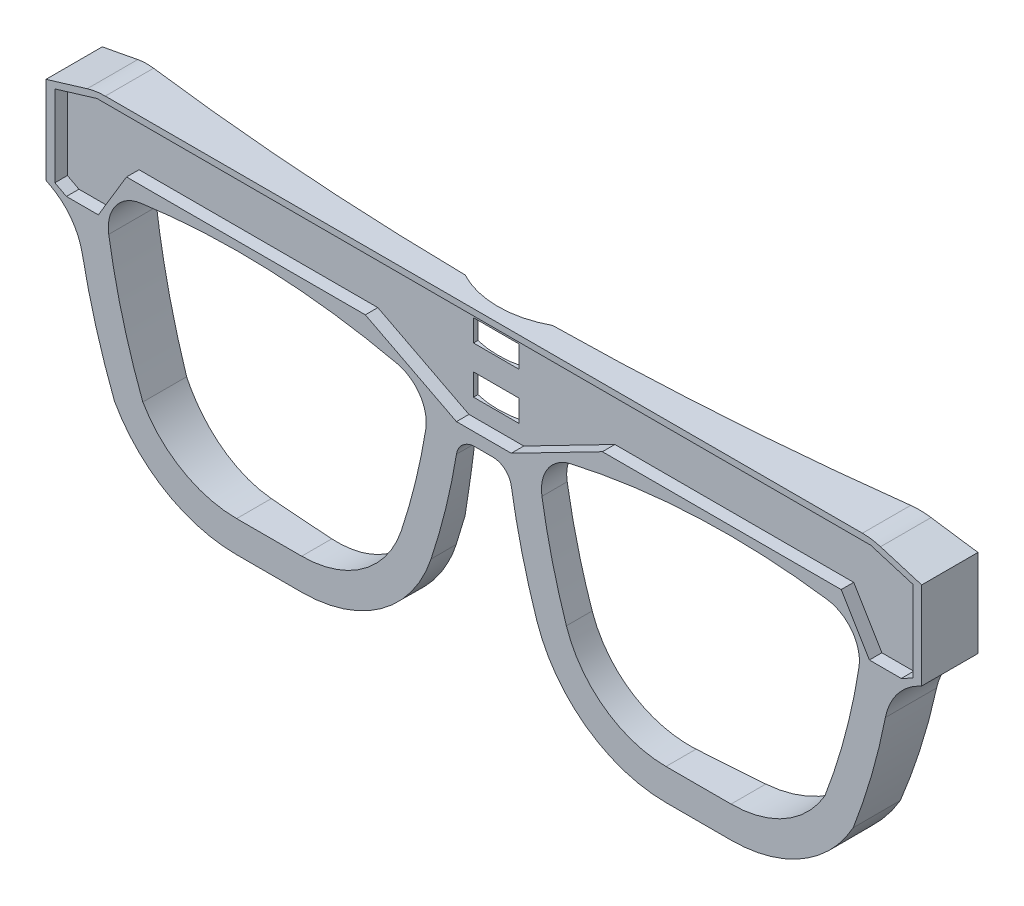
SolidWorks part; units mm, degrees
ref_plane "Front Plane" through (0, 0, 0) normal (0, 0, 1) x (1, 0, 0)
ref_plane "Top Plane" through (0, 0, 0) normal (0, 1, 0) x (1, 0, 0)
ref_plane "Right Plane" through (0, 0, 0) normal (1, 0, 0) x (0, 0, -1)
sketch "Sketch1" plane through (0, 0, 0) normal (0, 0, 1) x (1, 0, 0)
  line L4 (-70, 16.5826) -> (-70, 2.5826)
  line L5 (-70, 2.5826) -> (-65, -0.0353)
  line L6 (-39.5244, -34) -> (-29.1194, -34)
  line L7 (-4, 0) -> (0, 0)
  line L8 (0, 45.3197) -> (0, -37.9766) construction
  line L11 (-62, 19) -> (0, 19)
  line L12 (0, 19) -> (0, 0)
  line L13 (-70, 16.5826) -> (-62, 19)
  arc A2 (-8.4439, -19.0581) -> (-4, 0) centre (-111.6609, 15.057) ccw
  arc A3 (-65, -0.0353) -> (-59.0574, -22.499) centre (40.965, 15.9791) ccw
  arc A4 (-59.0574, -22.499) -> (-39.5244, -34) centre (-39.5244, -11.6623) ccw
  arc A5 (-29.1194, -34) -> (-8.4439, -19.0581) centre (-29.1194, -12.2244) ccw
  point P4 (-65, 21)
  point P7 (0, 0)
  point P20 (0, -37.9766)
  point P21 (-65, 19)
  point P22 (-70, 14.7143)
  point P23 (0, 0)
  point P24 (-70, 16.5826)
  dimension "D8" = 5
  dimension "D1" = 4
  dimension "D2" = 53
  dimension "D3" = 34
  dimension "D4" = 70
  dimension "D5" = 8
  dimension "D7" = 14
extrude "Boss-Extrude1" add sketch "Sketch1" along normal blind 9 contours L4 L5 A3 A4 L6 A5 A2 L7 L12 L11 L13
sketch "Sketch2" plane through (0, 0, 9) normal (0, 0, 1) x (1, 0, 0)
  line L7 (-39.5244, -29) -> (-29.1194, -29)
  line L8 (-39.5244, -29) -> (-29.1194, -29)
  arc A15 (-60.0561, 0.7118) -> (-59.2887, 6.3037) centre (-50.178, 2.2047) cw
  arc A16 (-59.2887, 6.3037) -> (-8.9375, 4.059) centre (-39.064, -105.8745) cw
  arc A17 (-8.9375, 4.059) -> (-8.9518, 0.6925) centre (-21.3647, 2.4286) cw
  arc A19 (-13.1913, -17.489) -> (-8.9518, 0.6925) centre (-111.6609, 15.057) ccw
  arc A20 (-29.1194, -29) -> (-13.1913, -17.489) centre (-29.1194, -12.2244) ccw
  arc A21 (-54.5219, -20.3612) -> (-39.5244, -29) centre (-39.5244, -11.6623) ccw
  arc A22 (-60.0561, 0.7118) -> (-54.5219, -20.3612) centre (40.965, 15.9791) ccw
  arc A23 (-13.1913, -17.489) -> (-8.9518, 0.6925) centre (-111.6609, 15.057) ccw
  arc A24 (-29.1194, -29) -> (-13.1913, -17.489) centre (-29.1194, -12.2244) ccw
  arc A25 (-54.5219, -20.3612) -> (-39.5244, -29) centre (-39.5244, -11.6623) ccw
  arc A26 (-60.0561, 0.7118) -> (-54.5219, -20.3612) centre (40.965, 15.9791) ccw
  point P5 (-58.6445, 7.3414)
  point P6 (-8.954, 4.0698)
  point P7 (-59.2984, 6.3081)
  dimension "D1" = 5
extrude "Cut-Extrude1" cut sketch "Sketch2" against normal through all
fillet "Fillet1" radius 6 2 edges at (-8.9375, 4.059, 4.5) (-59.2887, 6.3037, 4.5)
sketch "Sketch3" plane through (0, 0, 9) normal (0, 0, 1) x (1, 0, 0)
  line L0 (-68.579, 15.9673) -> (-61.8522, 18)
  line L1 (-70, 16.5826) -> (-62, 19) construction
  line L2 (-4.3821, 2) -> (4.3821, 2)
  line L4 (0, 2) -> (0, 18)
  line L5 (61.8522, 18) -> (-61.8522, 18)
  line L7 (-68.579, 15.9673) -> (-68.579, 2.9673)
  line L8 (-66.7315, 2) -> (-61.6323, 2)
  line L9 (-61.6323, 2) -> (-57.1269, 9.5)
  line L10 (-57.1269, 9.5) -> (-18.9511, 9.5)
  line L11 (-18.9511, 9.5) -> (-4.3821, 2)
  line L12 (-62, 19) -> (0, 19) construction
  line L13 (-4, 0) -> (0, 0) construction
  line L14 (-68.579, 2.9673) -> (-66.7315, 2)
  line L15 (-70, 2.5826) -> (-65, -0.0353) construction
  line L16 (68.579, 15.9673) -> (61.8522, 18)
  line L17 (18.9511, 9.5) -> (4.3821, 2)
  line L18 (57.1269, 9.5) -> (18.9511, 9.5)
  line L19 (61.6323, 2) -> (57.1269, 9.5)
  line L20 (66.7315, 2) -> (61.6323, 2)
  line L21 (68.579, 2.9673) -> (66.7315, 2)
  line L22 (68.579, 15.9673) -> (68.579, 2.9673)
  arc A1 (-13.8821, 5.2959) -> (-54.8725, 7.0107) centre (-39.064, -105.8745) ccw construction
  point P40 (-39.064, 8.1123)
  dimension "D2" = 2
  dimension "D1" = 1
  dimension "D3" = 8.5
  dimension "D4" = 1
  dimension "D5" = 1
fillet "Fillet4" radius 3 1 edges at (-4, 0, 4.5)
fillet "Fillet5" radius 10 2 edges at (-65, -0.0353, 4.5) (-62, 19, 4.5)
mirror "Mirror2" about plane through (0, 19, 9) normal (1, 0, 0) of "Fillet5", "Fillet4", "Boss-Extrude1", "Cut-Extrude1", "Fillet1"
extrude "Cut-Extrude2" cut sketch "Sketch3" against normal blind 2 contours L5 L0 L7 L14 L8 L9 L10 L11 L2 L17 L18 L19 L20 L21 L22 L16
sketch "Sketch4" plane through (0, 0, 7) normal (0, 0, 1) x (1, 0, 0)
  line L0 (-4.3821, 2) -> (4.3821, 2) construction
  line L1 (3.65, 15.75) -> (-3.65, 15.75)
  line L2 (3.65, 15.75) -> (3.65, 12.25)
  line L3 (3.65, 12.25) -> (-3.65, 12.25)
  line L4 (-3.65, 15.75) -> (-3.65, 12.25)
  line L5 (3.65, 15.75) -> (-3.65, 12.25) construction
  line L6 (3.65, 12.25) -> (-3.65, 15.75) construction
  line L7 (3.65, 8.25) -> (-3.65, 8.25)
  line L8 (3.65, 8.25) -> (3.65, 4.75)
  line L9 (3.65, 4.75) -> (-3.65, 4.75)
  line L10 (-3.65, 8.25) -> (-3.65, 4.75)
  line L11 (3.65, 8.25) -> (-3.65, 4.75) construction
  line L12 (3.65, 4.75) -> (-3.65, 8.25) construction
  point P0 (0, 14)
  point P5 (0, 6.5)
  point P10 (0, 0)
  dimension "D1" = 3.5
  dimension "D2" = 7.3
  dimension "D3" = 4.5
  dimension "D4" = 12
extrude "Cut-Extrude3" cut sketch "Sketch4" against normal through all
sketch "Sketch5" plane through (0, 19, 0) normal (0, 1, 0) x (1, 0, 0)
  line L0 (-60.5221, 0) -> (60.5221, 0) construction
  line L1 (7, -9) -> (-7, -9) construction
  line L2 (7, -9) -> (7, 0) construction
  line L3 (7, 0) -> (-7, 0) construction
  line L4 (-7, -9) -> (-7, 0) construction
  line L5 (7, -9) -> (-7, 0) construction
  line L6 (7, 0) -> (-7, -9) construction
  line L7 (-60.5221, -9) -> (60.5221, -9) construction
  line L8 (-70, 0) -> (70, 0)
  arc A0 (-70, 0) -> (-7, -5) centre (-0.2936, 478.9) ccw
  arc A1 (-7, -5) -> (7, -5) centre (0, 8.0985) ccw
  arc A2 (7, -5) -> (70, 0) centre (0.2936, 478.9) ccw
  point P0 (0, -4.5)
  dimension "D1" = 14
  dimension "D2" = 5
extrude "Cut-Extrude4" cut sketch "Sketch5" against normal through all
